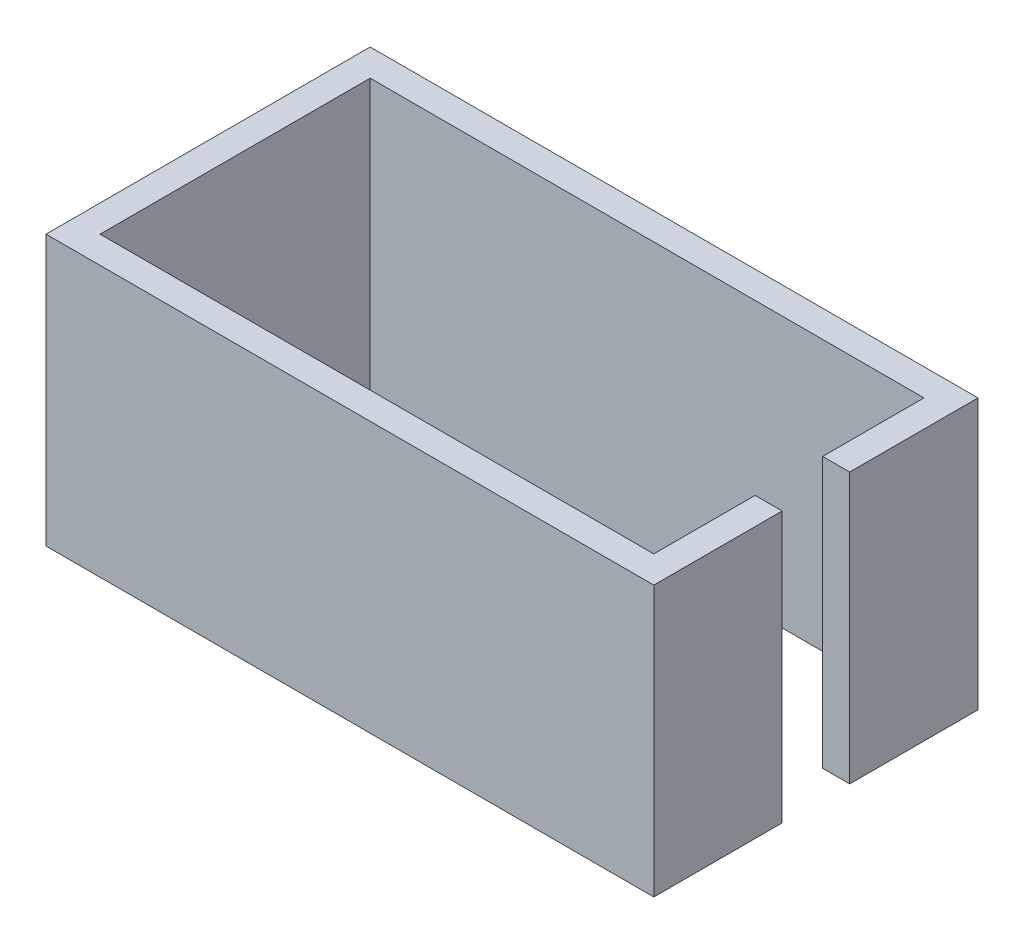
SolidWorks part; units mm, degrees
ref_plane "前视基准面" through (0, 0, 0) normal (0, 0, 1) x (1, 0, 0)
ref_plane "上视基准面" through (0, 0, 0) normal (0, 1, 0) x (1, 0, 0)
ref_plane "右视基准面" through (0, 0, 0) normal (1, 0, 0) x (0, 0, -1)
sketch "草图1" plane through (0, 0, 0) normal (0, 1, 0) x (1, 0, 0)
  line L0 (-11.25, 6) -> (11.25, 6)
  line L1 (-10.25, -5) -> (10.25, -5)
  line L2 (-10.25, -5) -> (-10.25, 5)
  line L3 (-10.25, 5) -> (10.25, 5)
  line L4 (10.25, -5) -> (10.25, 5)
  line L5 (-10.25, -5) -> (10.25, 5) construction
  line L6 (-10.25, 5) -> (10.25, -5) construction
  line L7 (11.25, -6) -> (11.25, 6)
  line L8 (-11.25, -6) -> (11.25, -6)
  line L9 (-11.25, -6) -> (-11.25, 6)
  point P0 (0, 0)
  dimension "D1" = 10
  dimension "D2" = 20.5
  dimension "D3" = 1
extrude "凸台-拉伸1" add sketch "草图1" along normal blind 10
sketch "草图2" plane through (11.25, 0, 0) normal (1, 0, 0) x (0, 0, -1)
  line L0 (-6, 0) -> (6, 0) construction
  line L1 (-1.25, 0) -> (1.25, 0)
  line L2 (-1.25, 0) -> (-1.25, 10)
  line L3 (-1.25, 10) -> (1.25, 10)
  line L4 (1.25, 0) -> (1.25, 10)
  line L5 (-6, 10) -> (6, 10) construction
  dimension "D1" = 2.5
extrude "切除-拉伸1" cut sketch "草图2" against normal blind 5
